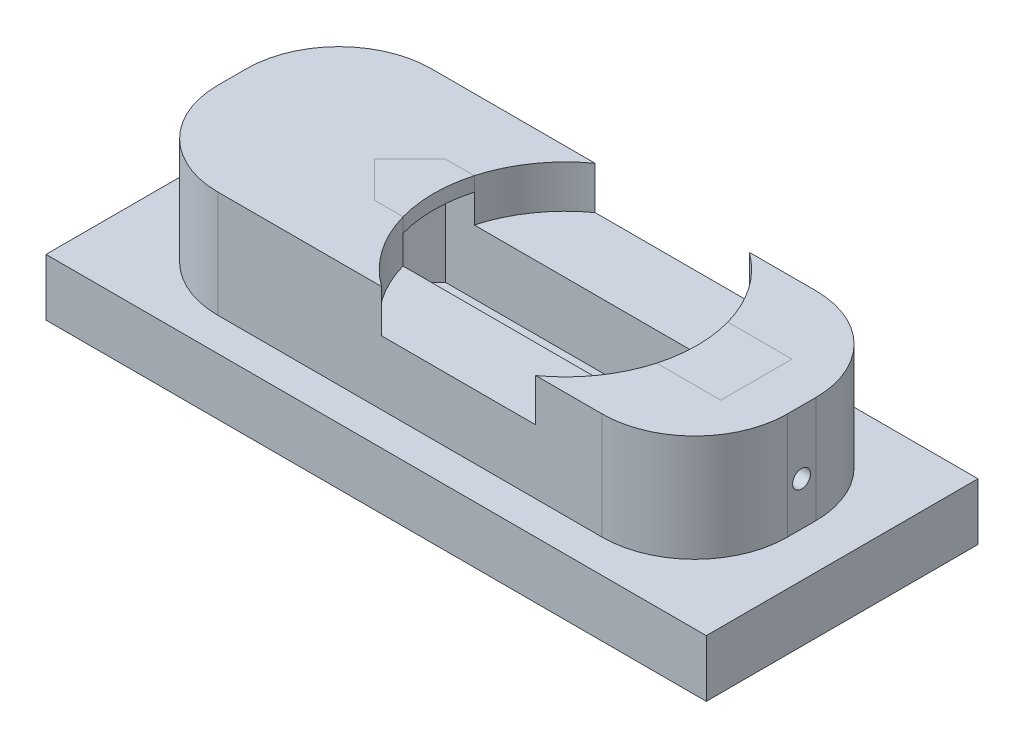
SolidWorks part; units mm, degrees
ref_plane "Front Plane" through (0, 0, 0) normal (0, 0, 1) x (1, 0, 0)
ref_plane "Top Plane" through (0, 0, 0) normal (0, 1, 0) x (1, 0, 0)
ref_plane "Right Plane" through (0, 0, 0) normal (1, 0, 0) x (0, 0, -1)
sketch "Sketch1" plane through (0, 0, 0) normal (0, 1, 0) x (1, 0, 0)
  line L1 (-40, -15) -> (40, -15)
  line L2 (-40, -15) -> (-40, 15)
  line L3 (-40, 15) -> (40, 15)
  line L4 (40, -15) -> (40, 15)
  line L5 (-40, -15) -> (40, 15) construction
  line L6 (-40, 15) -> (40, -15) construction
  point P0 (0, 0)
  dimension "D1" = 30
  dimension "D2" = 80
extrude "Boss-Extrude1" add sketch "Sketch1" along normal blind 60
sketch "Sketch2" plane through (0, 60, 0) normal (0, 1, 0) x (1, 0, 0)
  line L0 (-15, 5) -> (15, 5)
  line L3 (15, -5) -> (-15, -5)
  line L4 (-15, -5) -> (-20, 0)
  line L5 (-20, 0) -> (-15, 5)
  line L6 (15, 5) -> (33.657, 5)
  line L7 (33.657, 5) -> (33.657, -5)
  line L8 (33.657, -5) -> (15, -5)
  dimension "D1" = 15
  dimension "D2" = 15
  dimension "D3" = 15
  dimension "D4" = 15
  dimension "D5" = 5
  dimension "D6" = 5
extrude "Cut-Extrude1" cut sketch "Sketch2" against normal blind 75
sketch "Sketch3" plane through (-40, 0, 0) normal (-1, 0, 0) x (0, 0, 1)
  circle A0 centre (0, 51.112) radius 1.25
  dimension "D1" = 2.5
extrude "Cut-Extrude2" cut sketch "Sketch3" against normal through all and the other way through all
fillet "Fillet1" radius 13 4 edges at (40, 30, -15) (-40, 30, -15) (40, 30, 15) (-40, 30, 15)
ref_plane "Plane2" through (0, -10, 0) normal (0, -1, 0) x (-1, 0, 0)
sketch "Sketch15" plane through (0, -10, 0) normal (0, -1, 0) x (-1, 0, 0)
  line L1 (-41.9055, 15.8797) -> (41.7906, 15.8797)
  line L2 (-41.9055, 15.8797) -> (-41.9055, -15.8187)
  line L3 (-41.9055, -15.8187) -> (41.7906, -15.8187)
  line L4 (41.7906, 15.8797) -> (41.7906, -15.8187)
extrude "Cut-Extrude7" cut sketch "Sketch15" against normal blind 50
ref_plane "Plane3" through (0, 40, 0) normal (0, -1, 0) x (-1, 0, 0)
sketch "Sketch16" plane through (0, 40, 0) normal (0, -1, 0) x (-1, 0, 0)
  line L1 (-46.2811, 18.511) -> (46.4879, 18.511)
  line L2 (-46.2811, 18.511) -> (-46.2811, -19.6628)
  line L3 (-46.2811, -19.6628) -> (46.4879, -19.6628)
  line L4 (46.4879, 18.511) -> (46.4879, -19.6628)
extrude "Boss-Extrude4" add sketch "Sketch16" along normal blind 3 and the other way blind 5
ref_plane "Plane4" through (0, 60, 0) normal (0, 1, 0) x (1, 0, 0)
sketch "Sketch18" plane through (0, 60, 0) normal (0, 1, 0) x (1, 0, 0)
  circle A0 centre (6.8285, 0) radius 18.5
  dimension "D1" = 37
sketch "Sketch19" plane through (0, 60, 0) normal (0, 1, 0) x (1, 0, 0)
  line L0 (33.657, 5) -> (-15, 5) construction
  line L1 (-15, -5) -> (33.657, -5) construction
  line L2 (-10.983, 5) -> (-15, 5)
  line L3 (-15, 5) -> (-20, 0)
  line L4 (-20, 0) -> (-15, -5)
  line L5 (-15, -5) -> (-10.983, -5)
  line L6 (-15, -5) -> (33.657, -5) construction
  line L7 (24.64, 5) -> (33.657, 5)
  line L8 (33.657, 5) -> (33.657, -5)
  line L9 (33.657, -5) -> (24.64, -5)
  arc A0 (-10.983, 5) -> (-10.983, -5) centre (6.8285, 0) ccw
  circle A1 centre (6.8285, 0) radius 18.5 construction
  arc A2 (24.64, 5) -> (24.64, -5) centre (6.8285, 0) cw
extrude "Cut-Extrude8" cut sketch "Sketch18" against normal blind 6 contours A0
extrude "Boss-Extrude5" add sketch "Sketch19" against normal blind 2 separate body
